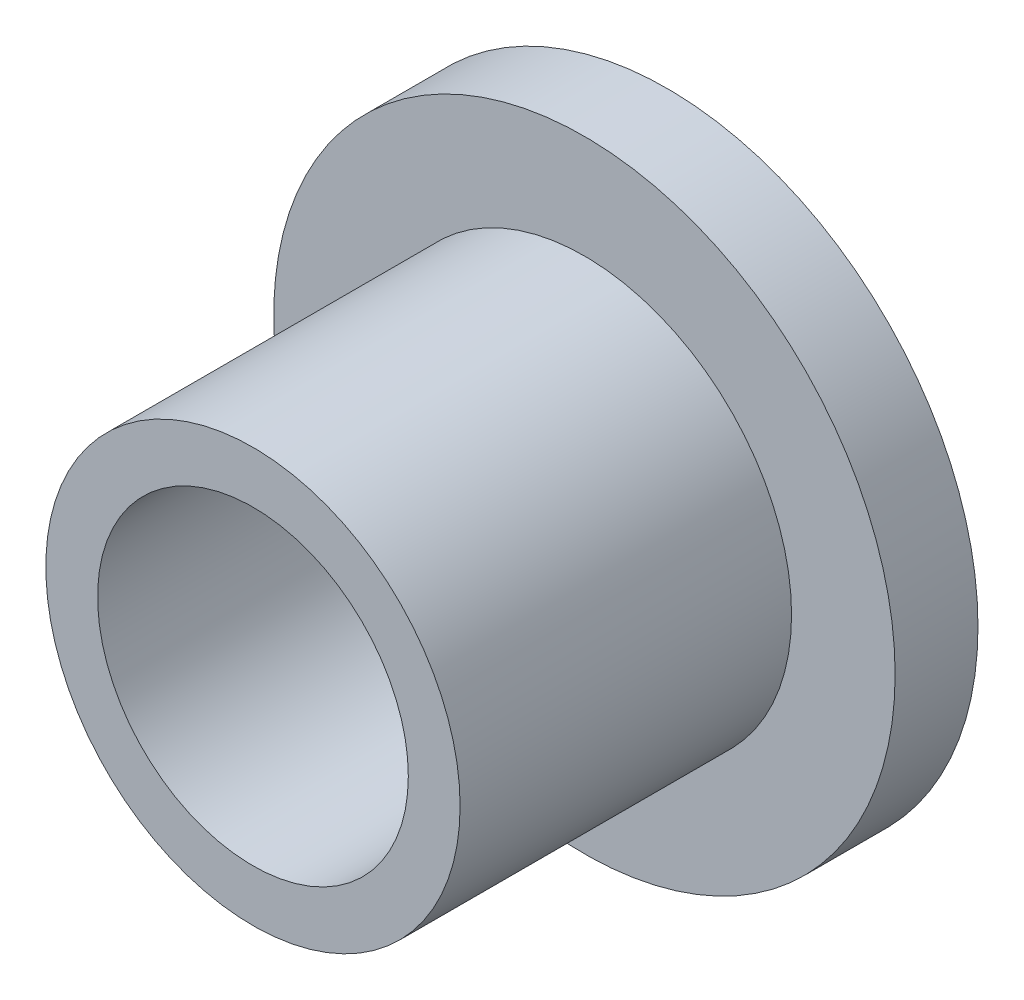
SolidWorks part; units mm, degrees
material "Leaded Commercial Bronze"
ref_plane "Front Plane" through (0, 0, 0) normal (0, 0, 1) x (1, 0, 0)
ref_plane "Top Plane" through (0, 0, 0) normal (0, 1, 0) x (1, 0, 0)
ref_plane "Right Plane" through (0, 0, 0) normal (1, 0, 0) x (0, 0, -1)
sketch "Sketch1" plane through (0, 0, 0) normal (0, 0, 1) x (1, 0, 0)
  circle A0 centre (0, 0) radius 9.525
  dimension "D1" = 19.05
extrude "Boss-Extrude1" add sketch "Sketch1" along normal blind 2.54
sketch "Sketch2" plane through (0, 0, 2.54) normal (0, 0, 1) x (1, 0, 0)
  circle A0 centre (0, 0) radius 6.35
  dimension "D1" = 12.7
extrude "Boss-Extrude3" add sketch "Sketch2" along normal blind 10.16
sketch "Sketch4" plane through (0, 0, 12.7) normal (0, 0, 1) x (1, 0, 0)
  circle A0 centre (0, 0) radius 4.7625
  dimension "D1" = 9.525
extrude "Cut-Extrude1" cut sketch "Sketch4" against normal blind 25.4
